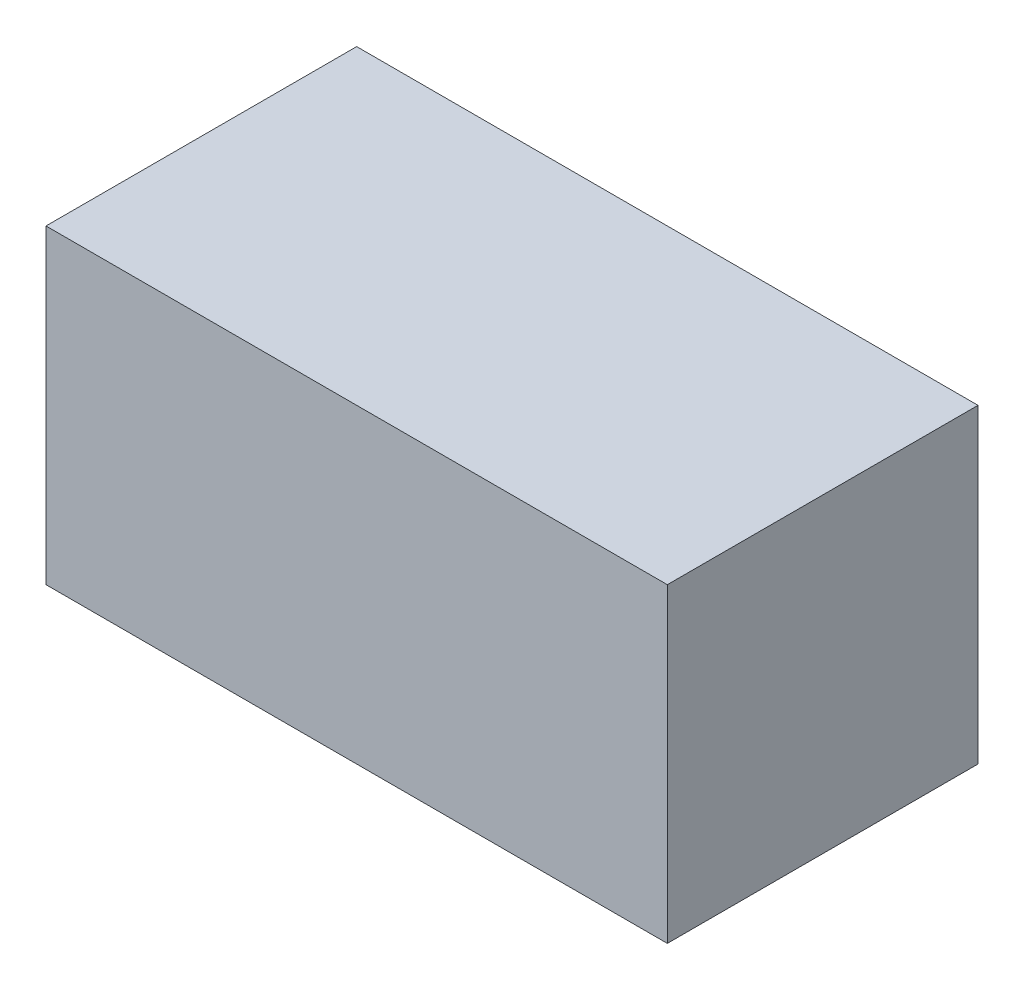
SolidWorks part; units mm, degrees
ref_plane "Front Plane" through (0, 0, 0) normal (0, 0, 1) x (1, 0, 0)
ref_plane "Top Plane" through (0, 0, 0) normal (0, 1, 0) x (1, 0, 0)
ref_plane "Right Plane" through (0, 0, 0) normal (1, 0, 0) x (0, 0, -1)
sketch "Sketch1" plane through (0, 0, 0) normal (0, 1, 0) x (1, 0, 0)
  line L1 (0, 0) -> (1.524, 0)
  line L2 (0, 0) -> (0, 0.762)
  line L3 (0, 0.762) -> (1.524, 0.762)
  line L4 (1.524, 0) -> (1.524, 0.762)
  dimension "D1" = 1.524
  dimension "D2" = 0.762
extrude "Boss-Extrude1" add sketch "Sketch1" along normal blind 0.762
